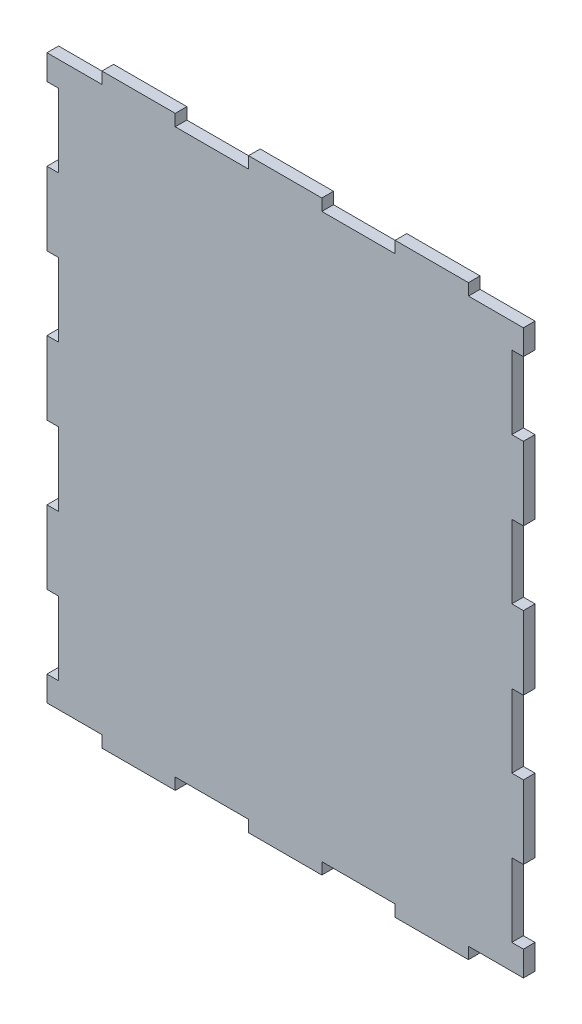
SolidWorks part; units mm, degrees
ref_plane "Front Plane" through (0, 0, 0) normal (0, 0, 1) x (1, 0, 0)
ref_plane "Top Plane" through (0, 0, 0) normal (0, 1, 0) x (1, 0, 0)
ref_plane "Right Plane" through (0, 0, 0) normal (1, 0, 0) x (0, 0, -1)
sketch "Sketch1" plane through (0, 0, 0) normal (0, 0, 1) x (1, 0, 0)
  line L1 (-75.9819, -3.175) -> (54.0181, -3.175)
  line L2 (-75.9819, -3.175) -> (-75.9819, 156.825)
  line L3 (-75.9819, 156.825) -> (54.0181, 156.825)
  line L4 (54.0181, -3.175) -> (54.0181, 156.825)
extrude "Boss-Extrude1" add sketch "Sketch1" against normal blind 3.175
sketch "Sketch2" plane through (0, 0, 0) normal (0, 0, 1) x (1, 0, 0)
  line L0 (-72.8069, 46.825) -> (-72.8069, 66.825) construction
  line L1 (-72.8069, 66.825) -> (-75.9819, 66.825) construction
  line L2 (-75.9819, 66.825) -> (-75.9819, 46.825) construction
  line L3 (-75.9819, 46.825) -> (-72.8069, 46.825) construction
  line L4 (-72.8069, 86.825) -> (-72.8069, 106.825) construction
  line L5 (-72.8069, 106.825) -> (-75.9819, 106.825) construction
  line L6 (-75.9819, 106.825) -> (-75.9819, 86.825) construction
  line L7 (-75.9819, 86.825) -> (-72.8069, 86.825) construction
  line L8 (-72.8069, 126.825) -> (-72.8069, 146.825) construction
  line L9 (-72.8069, 146.825) -> (-75.9819, 146.825) construction
  line L10 (-75.9819, 146.825) -> (-75.9819, 126.825) construction
  line L11 (-75.9819, 126.825) -> (-72.8069, 126.825) construction
  line L12 (-75.9819, 153.65) -> (-60.9819, 153.65) construction
  line L13 (-60.9819, 153.65) -> (-60.9819, 156.825) construction
  line L14 (-60.9819, 156.825) -> (-75.9819, 156.825) construction
  line L15 (-75.9819, 156.825) -> (-75.9819, 153.65) construction
  line L16 (-40.9819, 153.65) -> (-20.9819, 153.65) construction
  line L17 (-20.9819, 153.65) -> (-20.9819, 156.825) construction
  line L18 (-20.9819, 156.825) -> (-40.9819, 156.825) construction
  line L19 (-40.9819, 156.825) -> (-40.9819, 153.65) construction
  line L20 (-0.9819, 153.65) -> (19.0181, 153.65) construction
  line L21 (19.0181, 153.65) -> (19.0181, 156.825) construction
  line L22 (19.0181, 156.825) -> (-0.9819, 156.825) construction
  line L23 (-0.9819, 156.825) -> (-0.9819, 153.65) construction
  line L24 (54.0181, 156.825) -> (39.0181, 156.825) construction
  line L25 (39.0181, 156.825) -> (39.0181, 153.65) construction
  line L26 (39.0181, 153.65) -> (54.0181, 153.65) construction
  line L27 (54.0181, 153.65) -> (54.0181, 156.825) construction
  line L28 (54.0181, 126.825) -> (54.0181, 146.825) construction
  line L29 (54.0181, 146.825) -> (50.8431, 146.825) construction
  line L30 (50.8431, 146.825) -> (50.8431, 126.825) construction
  line L31 (50.8431, 126.825) -> (54.0181, 126.825) construction
  line L32 (54.0181, 86.825) -> (54.0181, 106.825) construction
  line L33 (54.0181, 106.825) -> (50.8431, 106.825) construction
  line L34 (50.8431, 106.825) -> (50.8431, 86.825) construction
  line L35 (50.8431, 86.825) -> (54.0181, 86.825) construction
  line L36 (54.0181, 46.825) -> (54.0181, 66.825) construction
  line L37 (54.0181, 66.825) -> (50.8431, 66.825) construction
  line L38 (50.8431, 66.825) -> (50.8431, 46.825) construction
  line L39 (50.8431, 46.825) -> (54.0181, 46.825) construction
  line L40 (54.0181, 6.825) -> (54.0181, 26.825) construction
  line L41 (54.0181, 26.825) -> (50.8431, 26.825) construction
  line L42 (50.8431, 26.825) -> (50.8431, 6.825) construction
  line L43 (50.8431, 6.825) -> (54.0181, 6.825) construction
  line L44 (54.0181, 0) -> (39.0181, 0) construction
  line L45 (39.0181, 0) -> (39.0181, -3.175) construction
  line L46 (39.0181, -3.175) -> (54.0181, -3.175) construction
  line L47 (54.0181, -3.175) -> (54.0181, 0) construction
  line L48 (19.0181, 0) -> (-0.9819, 0) construction
  line L49 (-0.9819, 0) -> (-0.9819, -3.175) construction
  line L50 (-0.9819, -3.175) -> (19.0181, -3.175) construction
  line L51 (19.0181, -3.175) -> (19.0181, 0) construction
  line L52 (-20.9819, 0) -> (-40.9819, 0) construction
  line L53 (-40.9819, 0) -> (-40.9819, -3.175) construction
  line L54 (-40.9819, -3.175) -> (-20.9819, -3.175) construction
  line L55 (-20.9819, -3.175) -> (-20.9819, 0) construction
  line L56 (-72.8069, 6.825) -> (-72.8069, 26.825) construction
  line L57 (-72.8069, 26.825) -> (-75.9819, 26.825) construction
  line L58 (-75.9819, 26.825) -> (-75.9819, 6.825) construction
  line L59 (-75.9819, 6.825) -> (-72.8069, 6.825) construction
  line L60 (-75.9819, -3.175) -> (-60.9819, -3.175) construction
  line L61 (-60.9819, -3.175) -> (-60.9819, 0) construction
  line L62 (-60.9819, 0) -> (-75.9819, 0) construction
  line L63 (-75.9819, 0) -> (-75.9819, -3.175) construction
  line L64 (-72.8069, 46.825) -> (-72.8069, 66.825)
  line L65 (-72.8069, 66.825) -> (-75.9819, 66.825)
  line L66 (-75.9819, 66.825) -> (-75.9819, 46.825)
  line L67 (-75.9819, 46.825) -> (-72.8069, 46.825)
  line L68 (-72.8069, 86.825) -> (-72.8069, 106.825)
  line L69 (-72.8069, 106.825) -> (-75.9819, 106.825)
  line L70 (-75.9819, 106.825) -> (-75.9819, 86.825)
  line L71 (-75.9819, 86.825) -> (-72.8069, 86.825)
  line L72 (-72.8069, 126.825) -> (-72.8069, 146.825)
  line L73 (-72.8069, 146.825) -> (-75.9819, 146.825)
  line L74 (-75.9819, 146.825) -> (-75.9819, 126.825)
  line L75 (-75.9819, 126.825) -> (-72.8069, 126.825)
  line L76 (-75.9819, 153.65) -> (-60.9819, 153.65)
  line L77 (-60.9819, 153.65) -> (-60.9819, 156.825)
  line L78 (-60.9819, 156.825) -> (-75.9819, 156.825)
  line L79 (-75.9819, 156.825) -> (-75.9819, 153.65)
  line L80 (-40.9819, 153.65) -> (-20.9819, 153.65)
  line L81 (-20.9819, 153.65) -> (-20.9819, 156.825)
  line L82 (-20.9819, 156.825) -> (-40.9819, 156.825)
  line L83 (-40.9819, 156.825) -> (-40.9819, 153.65)
  line L84 (-0.9819, 153.65) -> (19.0181, 153.65)
  line L85 (19.0181, 153.65) -> (19.0181, 156.825)
  line L86 (19.0181, 156.825) -> (-0.9819, 156.825)
  line L87 (-0.9819, 156.825) -> (-0.9819, 153.65)
  line L88 (54.0181, 156.825) -> (39.0181, 156.825)
  line L89 (39.0181, 156.825) -> (39.0181, 153.65)
  line L90 (39.0181, 153.65) -> (54.0181, 153.65)
  line L91 (54.0181, 153.65) -> (54.0181, 156.825)
  line L92 (54.0181, 126.825) -> (54.0181, 146.825)
  line L93 (54.0181, 146.825) -> (50.8431, 146.825)
  line L94 (50.8431, 146.825) -> (50.8431, 126.825)
  line L95 (50.8431, 126.825) -> (54.0181, 126.825)
  line L96 (54.0181, 86.825) -> (54.0181, 106.825)
  line L97 (54.0181, 106.825) -> (50.8431, 106.825)
  line L98 (50.8431, 106.825) -> (50.8431, 86.825)
  line L99 (50.8431, 86.825) -> (54.0181, 86.825)
  line L100 (54.0181, 46.825) -> (54.0181, 66.825)
  line L101 (54.0181, 66.825) -> (50.8431, 66.825)
  line L102 (50.8431, 66.825) -> (50.8431, 46.825)
  line L103 (50.8431, 46.825) -> (54.0181, 46.825)
  line L104 (54.0181, 6.825) -> (54.0181, 26.825)
  line L105 (54.0181, 26.825) -> (50.8431, 26.825)
  line L106 (50.8431, 26.825) -> (50.8431, 6.825)
  line L107 (50.8431, 6.825) -> (54.0181, 6.825)
  line L108 (54.0181, 0) -> (39.0181, 0)
  line L109 (39.0181, 0) -> (39.0181, -3.175)
  line L110 (39.0181, -3.175) -> (54.0181, -3.175)
  line L111 (54.0181, -3.175) -> (54.0181, 0)
  line L112 (19.0181, 0) -> (-0.9819, 0)
  line L113 (-0.9819, 0) -> (-0.9819, -3.175)
  line L114 (-0.9819, -3.175) -> (19.0181, -3.175)
  line L115 (19.0181, -3.175) -> (19.0181, 0)
  line L116 (-20.9819, 0) -> (-40.9819, 0)
  line L117 (-40.9819, 0) -> (-40.9819, -3.175)
  line L118 (-40.9819, -3.175) -> (-20.9819, -3.175)
  line L119 (-20.9819, -3.175) -> (-20.9819, 0)
  line L120 (-72.8069, 6.825) -> (-72.8069, 26.825)
  line L121 (-72.8069, 26.825) -> (-75.9819, 26.825)
  line L122 (-75.9819, 26.825) -> (-75.9819, 6.825)
  line L123 (-75.9819, 6.825) -> (-72.8069, 6.825)
  line L124 (-75.9819, -3.175) -> (-60.9819, -3.175)
  line L125 (-60.9819, -3.175) -> (-60.9819, 0)
  line L126 (-60.9819, 0) -> (-75.9819, 0)
  line L127 (-75.9819, 0) -> (-75.9819, -3.175)
extrude "Cut-Extrude1" cut sketch "Sketch2" against normal up to surface (3.175 mm away) up to face at (-10.9819, 76.825, -3.175)
